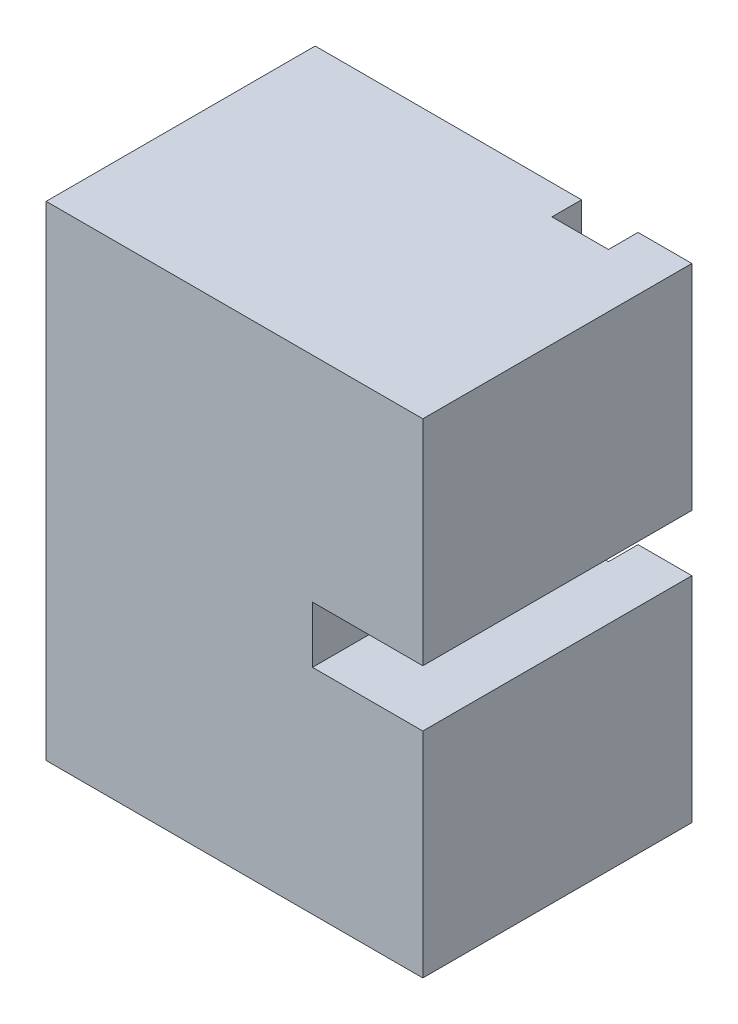
SolidWorks part; units mm, degrees
ref_plane "Přední rovina" through (0, 0, 0) normal (0, 0, 1) x (1, 0, 0)
ref_plane "Horní rovina" through (0, 0, 0) normal (0, 1, 0) x (1, 0, 0)
ref_plane "Pravá rovina" through (0, 0, 0) normal (1, 0, 0) x (0, 0, -1)
sketch "Skica1" plane through (0, 0, 0) normal (0, 0, 1) x (1, 0, 0)
  line L1 (0, 0) -> (70, 0)
  line L2 (0, 0) -> (0, 90)
  line L3 (0, 90) -> (70, 90)
  line L4 (70, 0) -> (70, 90)
  dimension "D1" = 90
  dimension "D2" = 70
extrude "Přidat vysunutím1" add sketch "Skica1" along normal blind 50
sketch "Skica7" plane through (0, 0, 0) normal (0, 0, -1) x (-1, 0, 0)
  line L0 (-70, 0) -> (-70, 90) construction
  line L1 (-70, 50.25) -> (-49.5, 50.25)
  line L2 (-70, 50.25) -> (-70, 39.75)
  line L3 (-70, 39.75) -> (-49.5, 39.75)
  line L4 (-49.5, 50.25) -> (-49.5, 39.75)
  line L5 (-70, 90) -> (0, 90) construction
  dimension "D1" = 20.5
  dimension "D2" = 10.5
  dimension "D3" = 39.75
extrude "Odebrat vysunutím3" cut sketch "Skica7" against normal blind 50
sketch "Skica9" plane through (0, 50.25, 0) normal (0, -1, 0) x (1, 0, 0)
  line L1 (49.5, 0) -> (60, 0)
  line L2 (49.5, 0) -> (49.5, 5.5)
  line L3 (49.5, 5.5) -> (60, 5.5)
  line L4 (60, 0) -> (60, 5.5)
  dimension "D1" = 10.5
  dimension "D2" = 5.5
extrude "Odebrat vysunutím4" cut sketch "Skica9" against normal blind 50 and the other way blind 60
